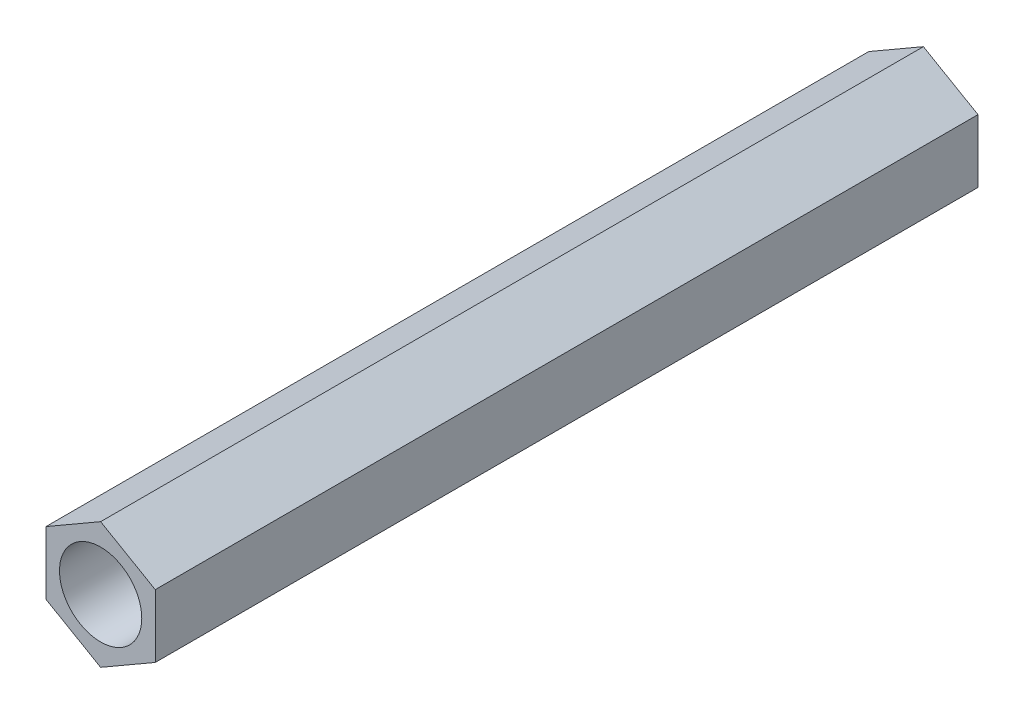
SolidWorks part; units mm, degrees
material "黄铜"
ref_plane "前视基准面" through (0, 0, 0) normal (0, 0, 1) x (1, 0, 0)
ref_plane "上视基准面" through (0, 0, 0) normal (0, 1, 0) x (1, 0, 0)
ref_plane "右视基准面" through (0, 0, 0) normal (1, 0, 0) x (0, 0, -1)
other "Configuration Table"
sketch "草图1" plane through (0, 0, 0) normal (0, 0, 1) x (1, 0, 0)
  line L0 (0, 0) -> (0, 3.2374) construction
  line L1 (0, 2.3) -> (-1.9919, 1.15)
  line L2 (-1.9919, 1.15) -> (-1.9919, -1.15)
  line L3 (-1.9919, -1.15) -> (0, -2.3)
  line L4 (0, -2.3) -> (1.9919, -1.15)
  line L5 (1.9919, -1.15) -> (1.9919, 1.15)
  line L6 (1.9919, 1.15) -> (0, 2.3)
  circle A0 centre (0, 0) radius 1.5
  circle A1 centre (0, 0) radius 1.9919 construction
  dimension "D1" = 3
  dimension "D2" = 4.6
extrude "凸台-拉伸1" add sketch "草图1" along normal blind 30
